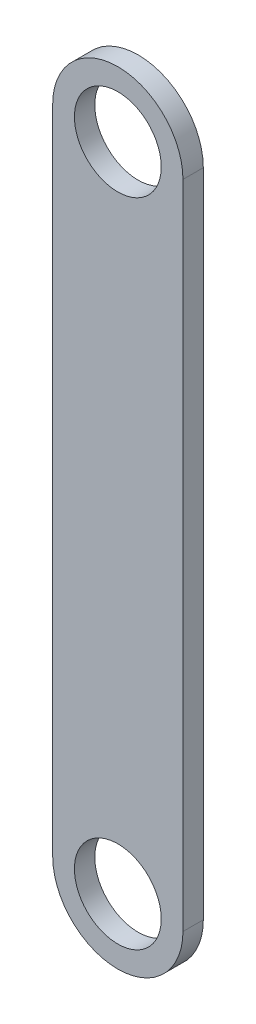
SolidWorks part; units mm, degrees
ref_plane "Front Plane" through (0, 0, 0) normal (0, 0, 1) x (1, 0, 0)
ref_plane "Top Plane" through (0, 0, 0) normal (0, 1, 0) x (1, 0, 0)
ref_plane "Right Plane" through (0, 0, 0) normal (1, 0, 0) x (0, 0, -1)
sketch "Sketch1" plane through (0, 0, 0) normal (0, 0, 1) x (1, 0, 0)
  line L0 (0, 0) -> (0, 127) construction
  line L1 (-12.7, 0) -> (-12.7, 127)
  line L2 (12.7, 0) -> (12.7, 127)
  arc A0 (-12.7, 0) -> (12.7, 0) centre (0, 0) ccw
  arc A1 (12.7, 127) -> (-12.7, 127) centre (0, 127) ccw
  circle A2 centre (0, 0) radius 8.4667
  circle A3 centre (0, 127) radius 8.4667
  point P3 (0, 63.5)
  dimension "D2" = 12.7
  dimension "D3" = 16.9333
  dimension "D1" = 127
extrude "Boss-Extrude1" add sketch "Sketch1" along normal blind 3.9688
scale "Scale1" scale about centroid uniform scaling yes scale factor 0.75
